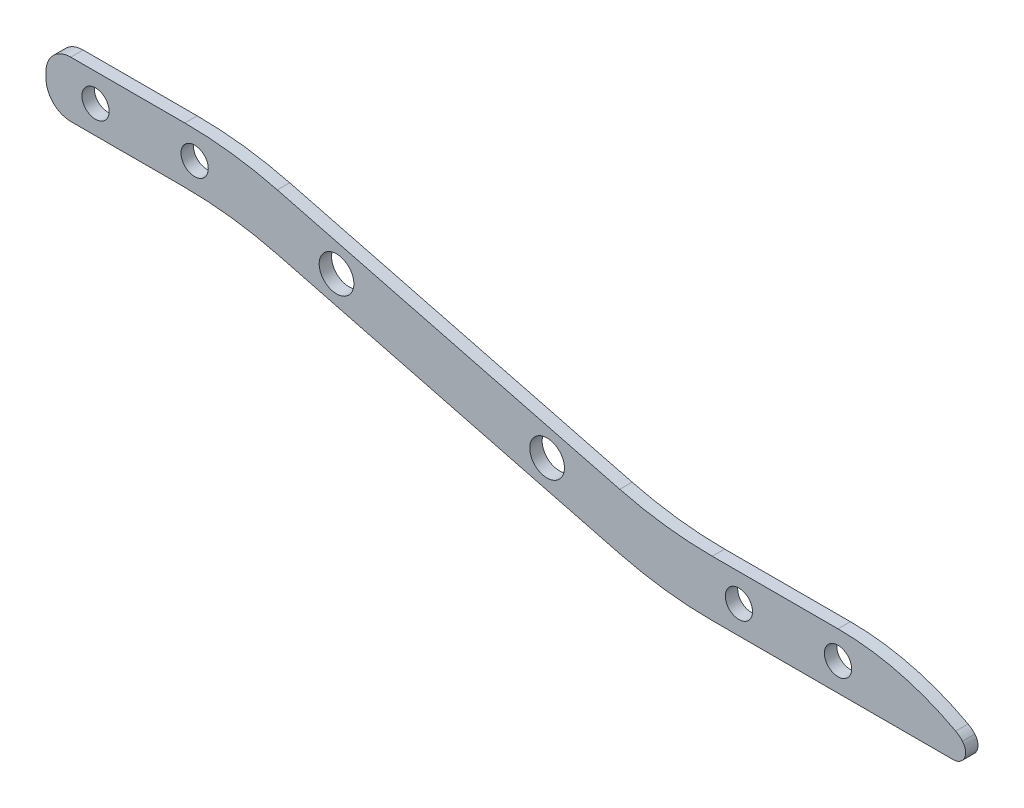
SolidWorks part; units mm, degrees
material "Thornel Mat VMA"
ref_plane "前视基准面" through (0, 0, 0) normal (0, 0, 1) x (1, 0, 0)
ref_plane "上视基准面" through (0, 0, 0) normal (0, 1, 0) x (1, 0, 0)
ref_plane "右视基准面" through (0, 0, 0) normal (1, 0, 0) x (0, 0, -1)
sketch "草图2" plane through (0, 0, 0) normal (0, 0, 1) x (1, 0, 0)
  line L0 (9.2004, -1.3048) -> (-18.4479, 5.8048)
  line L1 (-25.9191, 6.75) -> (-35.1237, 6.75)
  line L2 (-37.1237, 4.75) -> (-37.1237, 4.25)
  line L3 (-35.1237, 2.25) -> (-25.924, 2.25)
  line L4 (-18.4435, 1.3024) -> (9.15, -5.8024)
  line L5 (16.6304, -6.75) -> (36.1237, -6.75)
  line L6 (26.8215, -2.25) -> (16.6717, -2.25)
  circle A0 centre (26.8215, -4.5) radius 1.1
  circle A1 centre (18.8215, -4.5) radius 1.1
  circle A2 centre (-25.1237, 4.5) radius 1.1
  circle A3 centre (-33.1251, 4.5) radius 1.1
  arc A4 (-18.4479, 5.8048) -> (-25.9191, 6.75) centre (-25.9191, -23.25) ccw
  arc A5 (-35.1237, 6.75) -> (-37.1237, 4.75) centre (-35.1237, 4.75) ccw
  arc A6 (-37.1237, 4.25) -> (-35.1237, 2.25) centre (-35.1237, 4.25) ccw
  arc A7 (-18.4435, 1.3024) -> (-25.924, 2.25) centre (-25.924, -27.75) ccw
  arc A8 (9.15, -5.8024) -> (16.6304, -6.75) centre (16.6304, 23.25) ccw
  arc A9 (36.1237, -6.75) -> (36.8737, -5.0885) centre (36.1237, -5.75) ccw
  arc A10 (36.8737, -5.0885) -> (36.3241, -4.6517) centre (35.3738, -6.4115) ccw
  arc A11 (36.3241, -4.6517) -> (26.8215, -2.25) centre (26.8215, -22.25) ccw
  arc A12 (9.2004, -1.3048) -> (16.6717, -2.25) centre (16.6717, 27.75) ccw
extrude "凸台-拉伸1" add sketch "草图2" along normal blind 1
sketch "草图4" plane through (0, 0, 1) normal (0, 0, 1) x (1, 0, 0)
  line L0 (-18.4479, 5.8048) -> (-18.4435, 1.3024)
  line L1 (-18.4435, 1.3024) -> (9.15, -5.8024)
  line L2 (9.15, -5.8024) -> (9.2004, -1.3048)
  line L3 (9.2004, -1.3048) -> (-18.4479, 5.8048)
  line L4 (-4.6237, 2.25) -> (-5.7118, -1.9758) construction
  line L5 (-5.1678, 0.1371) -> (-18.4457, 3.5536) construction
  circle A0 centre (-13.6678, 2.3242) radius 1.4
  circle A1 centre (3.3322, -2.05) radius 1.4
  point P14 (0, 0)
  point P17 (0, 0)
  dimension "D1" = 2.8
  dimension "D2" = 2.8
  dimension "D3" = 8.5
  dimension "D4" = 8.5
  dimension "D5" = 4.5024
  dimension "D6" = 27.6484
  dimension "D7" = 75.523
extrude "切除-拉伸1" cut sketch "草图4" against normal through all contours A0 | A1
